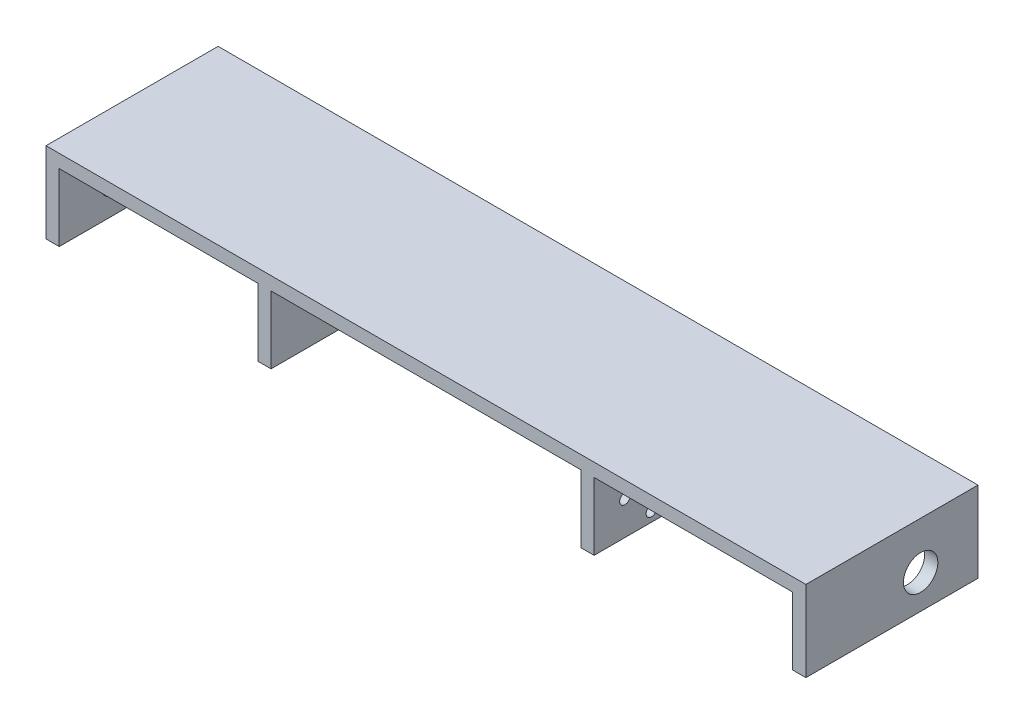
SolidWorks part; units mm, degrees
ref_plane "Front Plane" through (0, 0, 0) normal (0, 0, 1) x (1, 0, 0)
ref_plane "Top Plane" through (0, 0, 0) normal (0, 1, 0) x (1, 0, 0)
ref_plane "Right Plane" through (0, 0, 0) normal (1, 0, 0) x (0, 0, -1)
sketch "Sketch2" plane through (0, 0, 0) normal (0, 1, 0) x (1, 0, 0)
  line L1 (-42.6727, 74.2981) -> (244.3273, 74.2981)
  line L2 (-42.6727, 74.2981) -> (-42.6727, 9.2981)
  line L3 (-42.6727, 9.2981) -> (244.3273, 9.2981)
  line L4 (244.3273, 74.2981) -> (244.3273, 9.2981)
extrude "Boss-Extrude1" add sketch "Sketch2" along normal blind 5
sketch "Sketch4" plane through (0, 0, 0) normal (0, -1, 0) x (1, 0, 0)
  line L0 (-42.6727, -9.2981) -> (244.3273, -9.2981) construction
  line L1 (-42.6727, -74.2981) -> (-37.6727, -74.2981)
  line L2 (-42.6727, -74.2981) -> (-42.6727, -9.2981)
  line L3 (-42.6727, -9.2981) -> (-37.6727, -9.2981)
  line L4 (-37.6727, -74.2981) -> (-37.6727, -9.2981)
extrude "Boss-Extrude2" add sketch "Sketch4" along normal blind 25.5
sketch "Sketch5" plane through (0, 0, 0) normal (0, -1, 0) x (1, 0, 0)
  line L0 (-37.6727, -9.2981) -> (244.3273, -9.2981) construction
  line L1 (42.3273, -9.2981) -> (37.3273, -9.2981)
  line L2 (42.3273, -9.2981) -> (42.3273, -74.2981)
  line L3 (42.3273, -74.2981) -> (37.3273, -74.2981)
  line L4 (37.3273, -9.2981) -> (37.3273, -74.2981)
  line L5 (244.3273, -74.2981) -> (-37.6727, -74.2981) construction
  line L6 (-37.6727, -74.2981) -> (-37.6727, -9.2981) construction
  dimension "D1" = 80
  dimension "D2" = 5
extrude "Boss-Extrude3" add sketch "Sketch5" along normal blind 25.5 contours L2 L3 L4 L1
sketch "Sketch6" plane through (0, 0, 0) normal (0, -1, 0) x (1, 0, 0)
  line L0 (244.3273, -74.2981) -> (42.3273, -74.2981) construction
  line L1 (244.3273, -9.2981) -> (239.3273, -9.2981)
  line L2 (244.3273, -9.2981) -> (244.3273, -74.2981)
  line L3 (244.3273, -74.2981) -> (239.3273, -74.2981)
  line L4 (239.3273, -9.2981) -> (239.3273, -74.2981)
extrude "Boss-Extrude4" add sketch "Sketch6" along normal blind 25.5
sketch "Sketch7" plane through (-42.6727, 0, 0) normal (-1, 0, 0) x (0, 0, 1)
  line L0 (-9.2981, -25.5) -> (-74.2981, -25.5) construction
  line L1 (-9.2981, 5) -> (-9.2981, -25.5) construction
  circle A0 centre (-30.9648, -12.75) radius 6.5
  dimension "D1" = 12.75
  dimension "D2" = 21.6667
sketch "Sketch8" plane through (0, 0, 0) normal (0, -1, 0) x (1, 0, 0)
  line L0 (239.3273, -74.2981) -> (42.3273, -74.2981) construction
  line L1 (164.3273, -74.2981) -> (159.3273, -74.2981)
  line L2 (164.3273, -74.2981) -> (164.3273, -9.2981)
  line L3 (164.3273, -9.2981) -> (159.3273, -9.2981)
  line L4 (159.3273, -74.2981) -> (159.3273, -9.2981)
  line L5 (42.3273, -9.2981) -> (239.3273, -9.2981) construction
  line L6 (239.3273, -9.2981) -> (239.3273, -74.2981) construction
  dimension "D1" = 75
extrude "Boss-Extrude5" add sketch "Sketch8" along normal blind 25.5
sketch "Sketch9" plane through (244.3273, 0, 0) normal (1, 0, 0) x (0, 0, -1)
  line L0 (74.2981, 5) -> (74.2981, -25.5) construction
  line L1 (74.2981, -25.5) -> (9.2981, -25.5) construction
  circle A0 centre (52.6315, -12.75) radius 6.5
  dimension "D1" = 21.6667
  dimension "D2" = 12.75
extrude "Cut-Extrude1" cut sketch "Sketch7" against normal up to next
extrude "Cut-Extrude2" cut sketch "Sketch9" against normal up to next contours A0
sketch "Sketch10" plane through (37.3273, 0, 0) normal (-1, 0, 0) x (0, 0, 1)
  line L0 (-9.2981, -25.5) -> (-9.2981, 0) construction
  line L1 (-9.2981, -25.5) -> (-74.2981, -25.5) construction
  circle A0 centre (-30.9648, -12.75) radius 4.5
  dimension "D1" = 21.6667
  dimension "D2" = 12.75
sketch "Sketch11" plane through (164.3273, 0, 0) normal (1, 0, 0) x (0, 0, -1)
  line L0 (74.2981, -25.5) -> (74.2981, 0) construction
  line L1 (74.2981, -25.5) -> (9.2981, -25.5) construction
  circle A0 centre (52.6315, -12.75) radius 4.5
  dimension "D1" = 21.6667
  dimension "D2" = 12.75
extrude "Cut-Extrude3" cut sketch "Sketch11" against normal up to next
extrude "Cut-Extrude4" cut sketch "Sketch10" against normal up to next contours A0
sketch "Sketch14" plane through (159.3273, 0, 0) normal (-1, 0, 0) x (0, 0, 1)
  line L0 (-9.2981, -25.5) -> (-9.2981, 0) construction
  line L1 (-9.2981, -25.5) -> (-74.2981, -25.5) construction
  line L2 (-15.9681, -25.5) -> (-14.9681, -25.5)
  line L3 (-15.9681, -25.5) -> (-15.9681, 0)
  line L4 (-15.9681, 0) -> (-14.9681, 0)
  line L5 (-14.9681, -25.5) -> (-14.9681, 0)
  line L6 (-9.2981, 0) -> (-74.2981, 0) construction
  line L8 (-46.9681, -25.5) -> (-45.9681, -25.5)
  line L9 (-46.9681, -25.5) -> (-46.9681, 0)
  line L10 (-46.9681, 0) -> (-45.9681, 0)
  line L11 (-45.9681, -25.5) -> (-45.9681, 0)
  point P0 (-30.9681, -11.7464)
  dimension "D1" = 21.67
  dimension "D2" = 15
  dimension "D3" = 15
extrude "Boss-Extrude6" add sketch "Sketch14" along normal blind 1
sketch "Sketch15" plane through (159.3273, 0, 0) normal (-1, 0, 0) x (0, 0, 1)
  line L0 (-15.9681, 0) -> (-45.9681, 0) construction
  line L1 (-15.9681, 0) -> (-15.9681, -25.5) construction
  line L2 (-45.9681, -25.5) -> (-45.9681, 0) construction
  line L4 (-15.9681, -25.5) -> (-45.9681, -25.5) construction
  circle A0 centre (-20.9681, -12.75) radius 2
  circle A1 centre (-40.9681, -12.75) radius 2
  circle A2 centre (-30.9681, -21.75) radius 2
  circle A3 centre (-30.9681, -3.75) radius 2
  dimension "D2" = 5
  dimension "D3" = 5
  dimension "D4" = 15
  dimension "D6" = 3.75
  dimension "D1" = 12.75
  dimension "D5" = 3.75
extrude "Cut-Extrude6" cut sketch "Sketch15" against normal up to next
